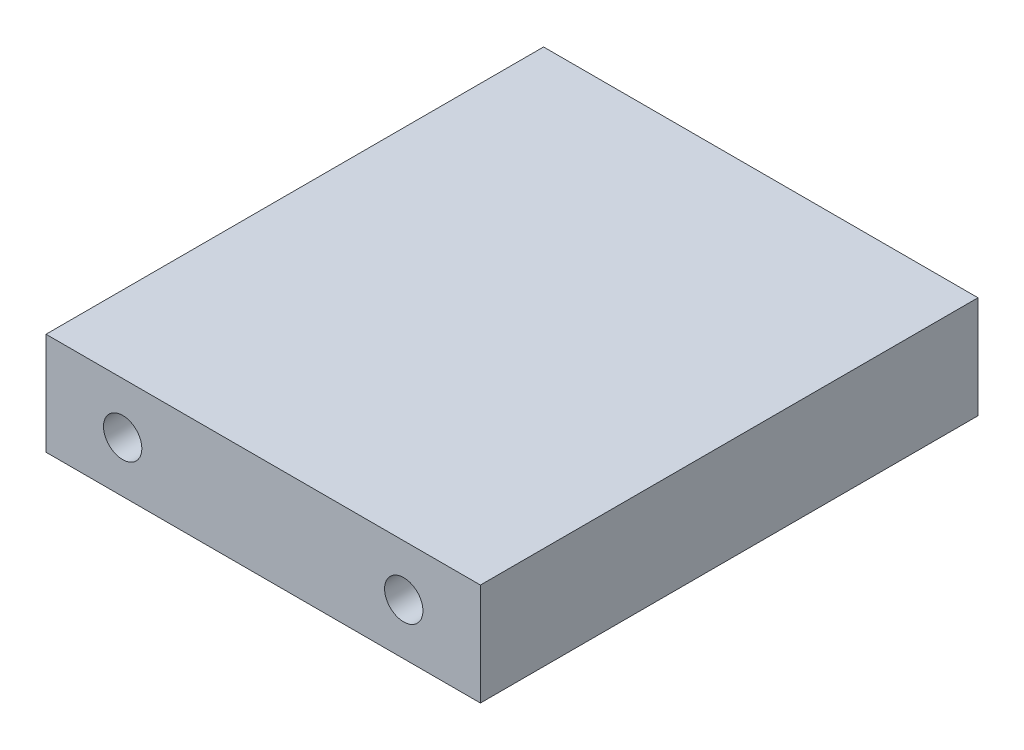
SolidWorks part; units mm, degrees
material "6061-T6 (SS)"
ref_plane "Front Plane" through (0, 0, 0) normal (0, 0, 1) x (1, 0, 0)
ref_plane "Top Plane" through (0, 0, 0) normal (0, 1, 0) x (1, 0, 0)
ref_plane "Right Plane" through (0, 0, 0) normal (1, 0, 0) x (0, 0, -1)
sketch "Sketch1" plane through (0, 0, 0) normal (0, 0, 1) x (1, 0, 0)
  line L1 (0, 0) -> (107.95, 0)
  line L2 (0, 0) -> (0, -25.4)
  line L3 (0, -25.4) -> (107.95, -25.4)
  line L4 (107.95, 0) -> (107.95, -25.4)
  line L5 (0, 0) -> (107.95, -25.4) construction
  line L6 (0, -25.4) -> (107.95, 0) construction
  point P5 (53.975, -12.7)
  dimension "D1" = 25.4
  dimension "D2" = 107.95
extrude "Boss-Extrude1" add sketch "Sketch1" along normal blind 123.65
sketch "Sketch2" plane through (0, 0, 123.65) normal (0, 0, 1) x (1, 0, 0)
  line L0 (0, -12.7) -> (107.95, -12.7) construction
  line L1 (0, 0) -> (0, -25.4) construction
  line L2 (107.95, -25.4) -> (107.95, 0) construction
  circle A0 centre (19.05, -12.7) radius 4.7625
  circle A1 centre (88.9, -12.7) radius 4.765
  dimension "D1" = 9.525
  dimension "D2" = 9.53
  dimension "D3" = 19.05
  dimension "D4" = 19.05
extrude "Cut-Extrude1" cut sketch "Sketch2" against normal blind 25.4
ref_plane "Plane1" through (0, 0, 61.825) normal (0, 0, 1) x (1, 0, 0)
mirror "Mirror1" about plane through (0, 0, 61.825) normal (0, 0, 1) of "Cut-Extrude1"
